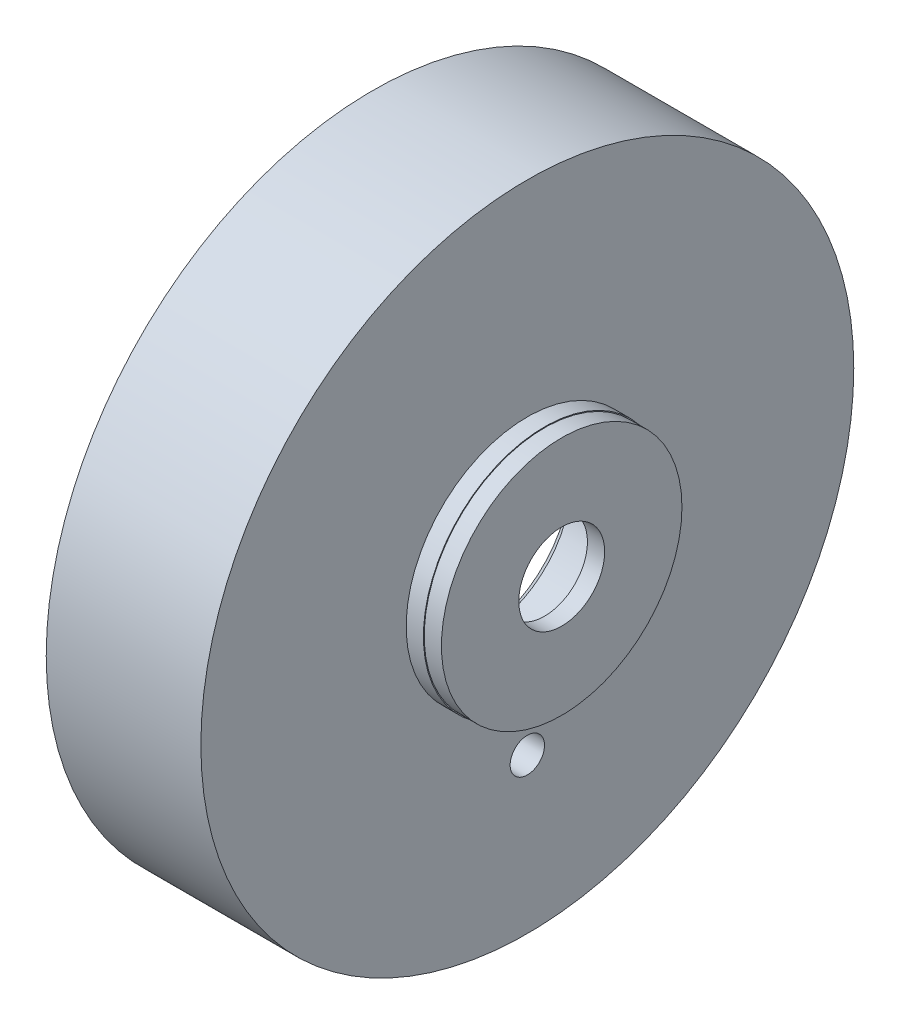
SolidWorks part; units mm, degrees
ref_plane "Plane1" through (0, 0, 0) normal (0, 0, 1) x (1, 0, 0)
ref_plane "Plane2" through (0, 0, 0) normal (0, 1, 0) x (1, 0, 0)
ref_plane "Plane3" through (0, 0, 0) normal (1, 0, 0) x (0, 0, -1)
sketch "HoldingSke" plane through (0, 0, 0) normal (0, 1, 0) x (1, 0, 0)
  line L0 (0, 0) -> (0.8387, -0.5446)
  line L1 (-15, 0) -> (100, 0) construction
  line L2 (0, 0) -> (-2.1039, 2.3779)
  line L3 (0, 0) -> (-11.863, 4.5341)
  line L4 (0, 0) -> (7.2428, 4.7035)
  line L5 (0, 0) -> (-23.7986, -8.8762)
  line L6 (0, 0) -> (-10.5278, -7.1032)
  line L7 (-2.1039, 2.3779) -> (3.3635, 27.1825)
  line L8 (-76.2, 3.3779) -> (-54.61, 3.3779)
  line L9 (-71.009, 38.7566) -> (-53.1078, 45.2721)
  line L10 (-76.2, 71.12) -> (104.1128, 71.12)
  line L11 (0, 0) -> (-5, 0)
  line L12 (-76.2, 101.6) -> (-76.162, 101.6)
  line L13 (24.9733, 27.94) -> (52.9518, 28.4284)
  line L14 (24.9733, 27.94) -> (24.9743, 27.94)
  line L15 (24.9733, 27.94) -> (100.4006, 29.5858)
  circle A0 centre (0, 0) radius 19
  circle A1 centre (0, 0) radius 12.7
  circle A2 centre (0, 0) radius 12.7
  dimension "MHD" = 25.4
  dimension "Hub_dia" = 25.4
  dimension "Diameter" = 38
  dimension "Num_teeth" = 33
  dimension "Pitch" = 1
  dimension "Overall_len" = 25.4
  dimension "Show_teeth" = 33
  dimension "Thickness" = 12.7
  dimension "OAL" = 25.4001
  dimension "T_dim" = 21.59
  dimension "Ap" = 20
  dimension "H" = 19.05
  dimension "Pitch_radius" = 180.3128
  dimension "Width" = 5
  dimension "Backlash" = 0.038
  dimension "Addendum_fac" = 1
  dimension "Dedendum_fac" = 1.25
  dimension "Clearance_fac" = 0.25
  dimension "Dedendum_add" = 0.001
  dimension "Module" = 1
sketch "BasProSke" plane through (0, 0, 0) normal (0, 1, 0) x (1, 0, 0)
  line L0 (-10, 0) -> (60, 0) construction
  line L1 (0, 15.5) -> (0, 19)
  line L2 (0, 15.5) -> (5, 15.5)
  line L3 (5, 15.5) -> (5, 19)
  line L4 (5, 19) -> (0, 19)
  dimension "Diameter" = 38
  dimension "Thickness" = 5
  dimension "Inside_diameter" = 31
revolve "Base-Revolve" add sketch "BasProSke" angle 360 about L0
sketch "TooCutSke" plane through (0, 0, 0) normal (1, 0, 0) x (0, 0, -1)
  line L3 (0.8801, 16.4765) -> (0.8801, 53.6633) construction
  line L4 (0, 0) -> (0, 59.563) construction
  line L5 (0, 0) -> (-6.4949, 68.0181) construction
  line L6 (-6.7635, 13.3721) -> (36.345, 17.4884) construction
  circle A0 centre (0, 0) radius 16.5 construction
  circle A1 centre (0, 0) radius 17.751 construction
  circle A2 centre (0, 0) radius 13.9544 construction
  circle A3 centre (0, 0) radius 15.4746 construction
  arc A4 (1.2267, 15.4259) -> (0.2294, 17.7495) centre (-6.7635, 13.3721) ccw
  arc A5 (1.2267, 15.4259) -> (-1.2267, 15.4259) centre (0, 0) ccw
  arc A6 (0.2294, 17.7495) -> (-0.2294, 17.7495) centre (0, 0) ccw
  arc A7 (-0.2294, 17.7495) -> (-1.2267, 15.4259) centre (6.7635, 13.3721) ccw
  dimension "Pitch_dia" = 33
  dimension "Base_dia" = 27.9089
  dimension "Root_dia" = 35.502
  dimension "Overcut_dia" = 30.9492
  dimension "Flank_rad" = 8.25
  dimension "Half_ang" = 5.455
  dimension "Half_CT" = 0.8801
extrude "ToothCut" cut sketch "TooCutSke" along normal through all
fillet "Breaks" [suppressed] radius 0.1
fillet "RootFillets" [suppressed] radius 0.251
pattern_circular "TeethCuts" count 33 every 10.909 about axis through (-10, 0, 0) along (1, 0, 0) of "RootFillets", "Breaks", "ToothCut"
sketch "Esquisse1" plane through (5, 0, 0) normal (1, 0, 0) x (0, 0, -1)
  circle A0 centre (0, 0) radius 19
  circle A2 centre (0, 0) radius 17.751
extrude "Boss.-Extru.1" add sketch "Esquisse1" along normal blind 1
sketch "Esquisse2" plane through (6, 0, 0) normal (1, 0, 0) x (0, 0, -1)
  circle A0 centre (0, 0) radius 19
  circle A1 centre (0, 0) radius 5.05
  dimension "D1" = 10.1
extrude "Boss.-Extru.2" add sketch "Esquisse2" along normal blind 3
sketch "Esquisse3" plane through (6, 0, 0) normal (-1, 0, 0) x (0, 0, 1)
  circle A0 centre (0, -10) radius 1
  circle A1 centre (0, 0) radius 5.05 construction
  dimension "D1" = 2
  dimension "D2" = 10
extrude "Enlèv. mat.-Extru.1" cut sketch "Esquisse3" against normal through all
sketch "Esquisse4" plane through (6, 0, 0) normal (-1, 0, 0) x (0, 0, 1)
  circle A0 centre (0, -10) radius 2
  dimension "D1" = 4
extrude "Enlèv. mat.-Extru.2" cut sketch "Esquisse4" against normal blind 1.5
sketch "Esquisse5" plane through (9, 0, 0) normal (1, 0, 0) x (0, 0, -1)
  circle A0 centre (0, 0) radius 5.05
  circle A1 centre (0, 0) radius 7.05
  dimension "D1" = 2
  dimension "D2" = 10.1
extrude "Boss.-Extru.4" add sketch "Esquisse5" along normal blind 1
sketch "Esquisse6" plane through (10, 0, 0) normal (1, 0, 0) x (0, 0, -1)
  circle A0 centre (0, 0) radius 7
  circle A1 centre (0, 0) radius 2.5
  dimension "D1" = 5
extrude "Boss.-Extru.5" add sketch "Esquisse6" along normal blind 1
chamfer "Chanfrein1" distance 0.5 angle 45 1 edges at (6, 0, -5.05)
equation "' \"Module@HoldingSke\" = 6.35"
equation "' \"Num_teeth@HoldingSke\" = 24"
equation "' \"Ap@HoldingSke\" =  14.5"
equation "' \"Ap@HoldingSke\" = 14.5"
equation "' \"Width@HoldingSke\" = 12"
equation "' \"Diameter@HoldingSke\" = 8 * 25.4"
equation "' \"Show_teeth@HoldingSke\" = 100"
equation "' \"Backlash@HoldingSke\" = 0.009 * 25.4"
equation "' \"Addendum_fac@HoldingSke\" = 1.0"
equation "' \"Dedendum_fac@HoldingSke\" = 1.25"
equation "' \"Dedendum_add@HoldingSke\" = 0.00005 * 25.4"
equation "' \"Clearance_fac@HoldingSke\" = 0.25"
equation "\"Pitch@HoldingSke\" = 1 / \"Module@HoldingSke\" "
equation "\"Overcut_dia@TooCutSke\" = (\"Num_teeth@HoldingSke\" - 2 * \"Addendum_fac@HoldingSke\") / \"Pitch@HoldingSke\" - 0.002 * 25.4"
equation "\"Pitch_dia@TooCutSke\" = \"Num_teeth@HoldingSke\" / \"Pitch@HoldingSke\""
equation "\"Base_dia@TooCutSke\" = \"Num_teeth@HoldingSke\" / \"Pitch@HoldingSke\" * cos((\"Ap@HoldingSke\"  * 3.14159265 / 180)) * 0.90"
equation "\"Root_dia@TooCutSke\" = \"Num_teeth@HoldingSke\"  / \"Pitch@HoldingSke\" + 2 *  \"Dedendum_fac@HoldingSke\"/ \"Pitch@HoldingSke\" + \"Dedendum_add@HoldingSke\" * 2"
equation "\"Half_ang@TooCutSke\" = 180 / \"Num_teeth@HoldingSke\""
equation "\"Half_CT@TooCutSke\" = \"Num_teeth@HoldingSke\" / \"Pitch@HoldingSke\" * sin((3.14159265 / 2 / \"Num_teeth@HoldingSke\")) / 2 + 10 * \"Backlash@HoldingSke\" / 4"
equation "\"Flank_rad@TooCutSke\" = \"Num_teeth@HoldingSke\" / \"Pitch@HoldingSke\" / 4"
equation "\"Radius@RootFillets\"= \"Clearance_fac@HoldingSke\" / \"Pitch@HoldingSke\" + \"Dedendum_add@HoldingSke\""
equation "\"Break_rad@Breaks\" = 0.02 / \"Pitch@HoldingSke\" * 5"
equation "\"Num_teeth@TeethCuts\" = int( \"Show_teeth@HoldingSke\" ) + 1"
equation "\"Num_teeth@TeethCuts\" = ((sgn( \"Num_teeth@TeethCuts\" - \"Num_teeth@HoldingSke\" )-1)*( \"Num_teeth@TeethCuts\" - \"Num_teeth@HoldingSke\" ))/-2+ \"Num_teeth@HoldingSke\""
equation "\"Num_teeth@TeethCuts\" = ((sgn( \"Num_teeth@TeethCuts\" - 2.0)+1)*( \"Num_teeth@TeethCuts\" - 2.0))/2 +2.0"
equation "\"Angle@TeethCuts\" = 360.0 / \"Num_teeth@HoldingSke\""
equation "\"Diameter@BasProSke\" = \"Num_teeth@HoldingSke\"  / \"Pitch@HoldingSke\" + 2 *  \"Dedendum_fac@HoldingSke\"/ \"Pitch@HoldingSke\" + \"Dedendum_add@HoldingSke\" * 2 + 0.002 * 25.4"
equation "\"Diameter@BasProSke\" = ((sgn( \"Diameter@BasProSke\"  - \"Diameter@HoldingSke\" )+1)*( \"Diameter@BasProSke\"  - \"Diameter@HoldingSke\" ))/2 + \"Diameter@HoldingSke\""
equation "\"Inside_diameter@BasProSke\" =  (\"Num_teeth@HoldingSke\" - 2 * \"Addendum_fac@HoldingSke\") / \"Pitch@HoldingSke\" "
equation "\"Thickness@BasProSke\"  = \"Width@HoldingSke\""
